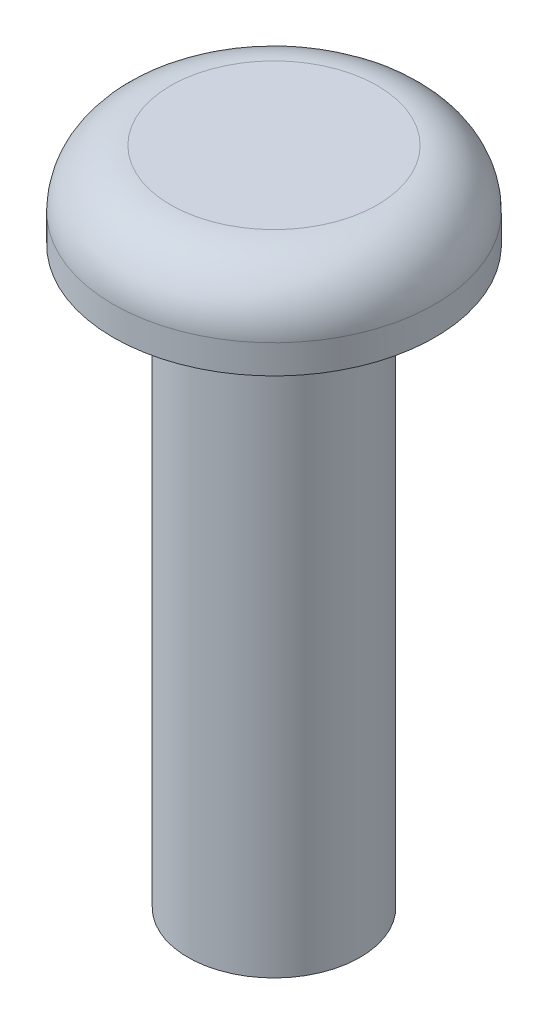
SolidWorks part; units mm, degrees
ref_plane "Front Plane" through (0, 0, 0) normal (0, 0, 1) x (1, 0, 0)
ref_plane "Top Plane" through (0, 0, 0) normal (0, 1, 0) x (1, 0, 0)
ref_plane "Right Plane" through (0, 0, 0) normal (1, 0, 0) x (0, 0, -1)
sketch "Sketch1" plane through (0, 0, 0) normal (0, 1, 0) x (1, 0, 0)
  circle A0 centre (0, 0) radius 2.8
  dimension "D1" = 5.6
extrude "Boss-Extrude1" add sketch "Sketch1" along normal blind 1.5
fillet "Fillet1" radius 1 1 edges at (0, 1.5, 2.8)
sketch "Sketch2" plane through (0, 0, 0) normal (0, -1, 0) x (1, 0, 0)
  circle A0 centre (0, 0) radius 1.5
  dimension "D1" = 3
extrude "Boss-Extrude2" add sketch "Sketch2" along normal blind 10
